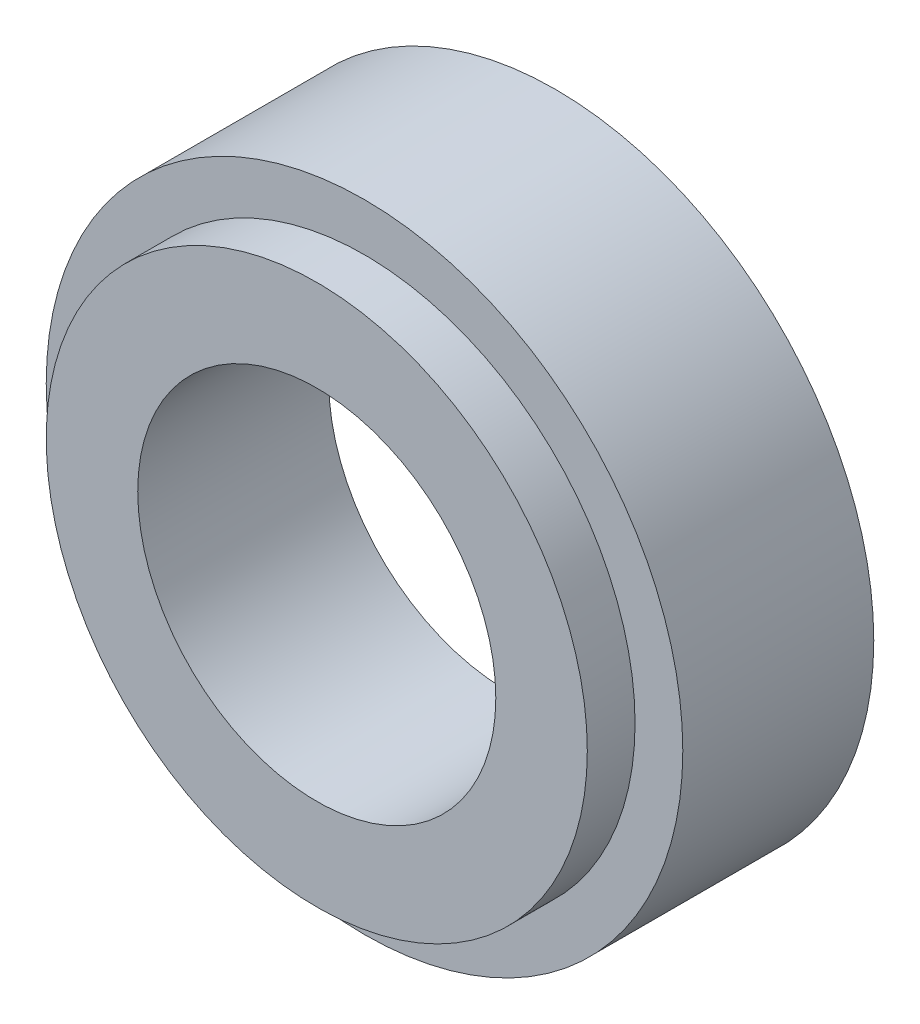
SolidWorks part; units mm, degrees
ref_plane "前视基准面" through (0, 0, 0) normal (0, 0, 1) x (1, 0, 0)
ref_plane "上视基准面" through (0, 0, 0) normal (0, 1, 0) x (1, 0, 0)
ref_plane "右视基准面" through (0, 0, 0) normal (1, 0, 0) x (0, 0, -1)
sketch "草图1" plane through (0, 0, 0) normal (0, 0, 1) x (1, 0, 0)
  circle A0 centre (0, 0) radius 20
  dimension "D1" = 40
extrude "拉伸1" add sketch "草图1" along normal blind 18
sketch "草图2" plane through (0, 0, 18) normal (0, 0, 1) x (1, 0, 0)
  circle A0 centre (0, 0) radius 20
  dimension "D1" = 40
extrude "切除-拉伸1" cut sketch "草图2" against normal blind 3
sketch "草图5" plane through (0, 0, 15) normal (0, 0, 1) x (1, 0, 0)
  circle A0 centre (0, 0) radius 20
  circle A1 centre (0, 0) radius 17
  dimension "D1" = 34
  dimension "D2" = 40
extrude "切除-拉伸4" cut sketch "草图5" against normal blind 3
sketch "草图6" plane through (0, 0, 0) normal (0, 0, -1) x (-1, 0, 0)
  circle A0 centre (0, 0) radius 11.25
extrude "切除-拉伸5" cut sketch "草图6" against normal blind 50
sketch "草图7" plane through (0, 0, 0) normal (0, 0, -1) x (-1, 0, 0)
  circle A0 centre (0, 0) radius 18
extrude "切除-拉伸6" cut sketch "草图7" against normal blind 3
